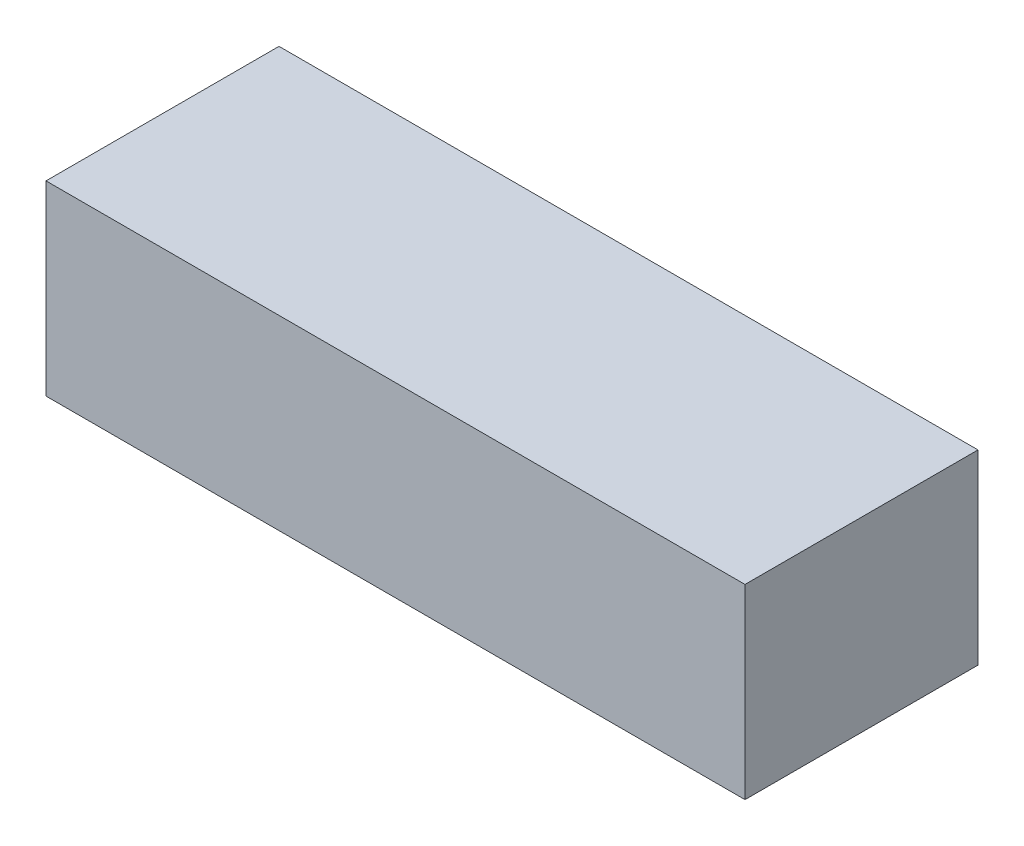
SolidWorks part; units mm, degrees
ref_plane "Спереди" through (0, 0, 0) normal (0, 0, 1) x (1, 0, 0)
ref_plane "Сверху" through (0, 0, 0) normal (0, 1, 0) x (1, 0, 0)
ref_plane "Справа" through (0, 0, 0) normal (1, 0, 0) x (0, 0, -1)
sketch "Эскиз1" plane through (0, 0, 0) normal (0, 0, 1) x (1, 0, 0)
  line L1 (0, 0) -> (30, 0)
  line L2 (0, 0) -> (0, 8)
  line L3 (0, 8) -> (30, 8)
  line L4 (30, 0) -> (30, 8)
  dimension "D1" = 8
  dimension "D2" = 30
extrude "Бобышка-Вытянуть1" add sketch "Эскиз1" along normal blind 10
